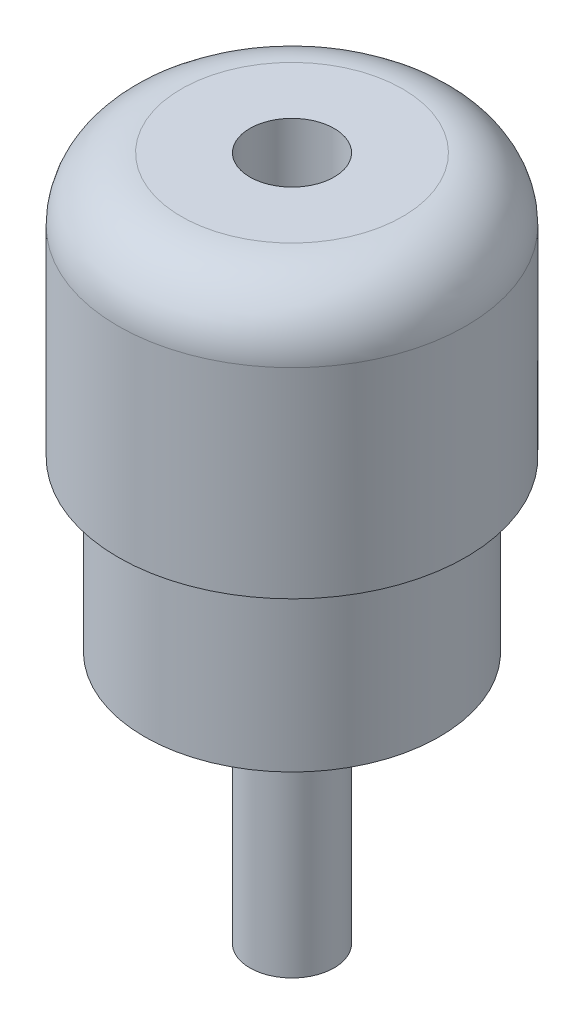
SolidWorks part; units mm, degrees
ref_plane "Alzado" through (0, 0, 0) normal (0, 0, 1) x (1, 0, 0)
ref_plane "Planta" through (0, 0, 0) normal (0, 1, 0) x (1, 0, 0)
ref_plane "Vista lateral" through (0, 0, 0) normal (1, 0, 0) x (0, 0, -1)
sketch "Croquis1" plane through (0, 0, 0) normal (0, 0, 1) x (1, 0, 0)
  line L0 (0, 0) -> (2, 0)
  line L1 (2, 0) -> (2, 12)
  line L2 (2, 12) -> (7, 12)
  line L3 (7, 12) -> (7, 20)
  line L4 (7, 20) -> (8.25, 20)
  line L5 (8.25, 20) -> (8.25, 32.5)
  line L6 (8.25, 32.5) -> (0, 32.5)
  line L7 (0, 32.5) -> (0, 0)
  dimension "D1" = 12
  dimension "D2" = 2
  dimension "D3" = 8
  dimension "D4" = 5
  dimension "D5" = 6.25
  dimension "D6" = 12.5
revolve "Revolución1" add sketch "Croquis1" angle 360 about L7
sketch "Croquis2" plane through (0, 32.5, 0) normal (0, 1, 0) x (1, 0, 0)
  circle A0 centre (0, 0) radius 2
  dimension "D1" = 4
extrude "Cortar-Extruir1" cut sketch "Croquis2" against normal blind 10
fillet "Redondeo1" radius 3 1 edges at (0, 32.5, 8.25)
